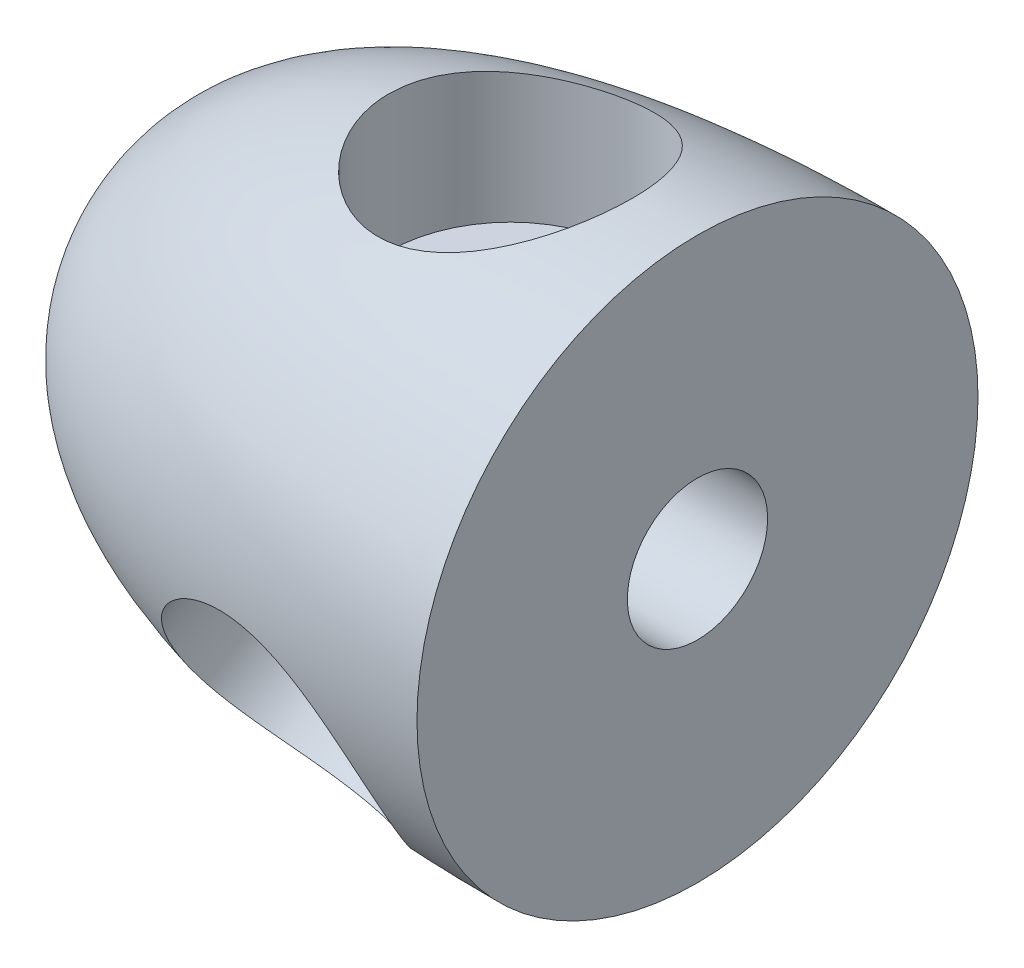
SolidWorks part; units mm, degrees
ref_plane "Front Plane" through (0, 0, 0) normal (0, 0, 1) x (1, 0, 0)
ref_plane "Top Plane" through (0, 0, 0) normal (0, 1, 0) x (1, 0, 0)
ref_plane "Right Plane" through (0, 0, 0) normal (1, 0, 0) x (0, 0, -1)
sketch "Sketch2" plane through (0, 0, 0) normal (0, 0, 1) x (1, 0, 0)
  line L0 (0, 0) -> (-38.1, 0)
  line L1 (0, 0) -> (0, 19.05)
  line L2 (-38.1, 0) -> (-38.1, 19.05) construction
  line L3 (0, 19.05) -> (-38.1, 19.05) construction
  spline S0 degree 3 poles (0, 19.05) (-14.199, 19.05) (-38.1, 16.9337) (-38.1, 0) knots 0 0 0 0 1 1 1 1
  point P3 (0, 0)
  dimension "D1" = 38.1
  dimension "D2" = 19.05
revolve "Revolve1" add sketch "Sketch2" angle 360 about L0
sketch "Sketch3" plane through (0, 0, 0) normal (1, 0, 0) x (0, 0, -1)
  circle A0 centre (0, 0) radius 4.7625
  dimension "D1" = 9.525
extrude "Cut-Extrude1" cut sketch "Sketch3" against normal blind 12.7 contours A0
ref_plane "Plane1" through (0, 7.62, 0) normal (0, 1, 0) x (1, 0, 0)
sketch "Sketch4" plane through (0, 7.62, 0) normal (0, 1, 0) x (1, 0, 0)
  circle A0 centre (-12.7, 0) radius 8.255
  dimension "D1" = 16.51
  dimension "D2" = 12.7
extrude "Cut-Extrude2" cut sketch "Sketch4" along normal blind 21.844
pattern_circular "CirPattern1" count 3 over 360 about axis through (0, 0, 0) along (1, 0, 0) of "Cut-Extrude2"
